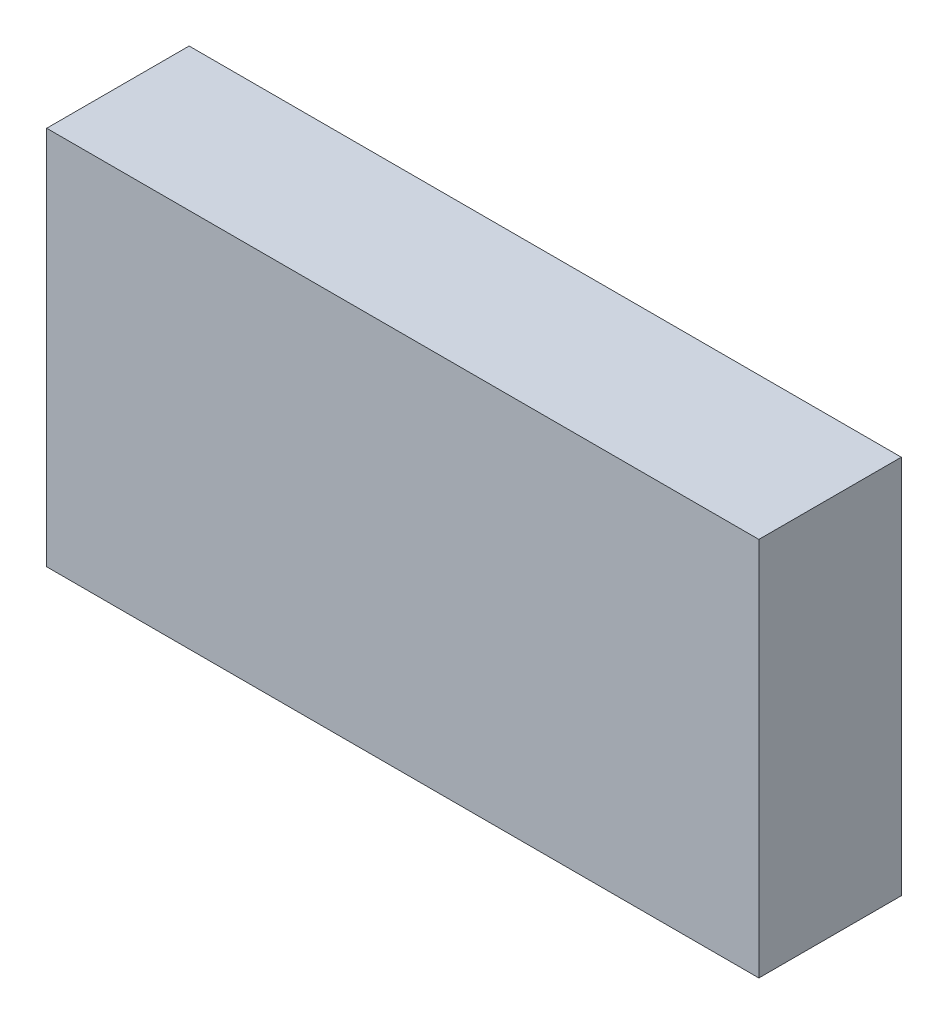
SolidWorks part; units mm, degrees
ref_plane "Front Plane" through (0, 0, 0) normal (0, 0, 1) x (1, 0, 0)
ref_plane "Top Plane" through (0, 0, 0) normal (0, 1, 0) x (1, 0, 0)
ref_plane "Right Plane" through (0, 0, 0) normal (1, 0, 0) x (0, 0, -1)
other "Configuration Table"
sketch "Sketch1" plane through (0, 0, 0) normal (0, 0, 1) x (1, 0, 0)
  line L1 (596, 73) -> (611, 73)
  line L2 (596, 73) -> (596, 81)
  line L3 (596, 81) -> (611, 81)
  line L4 (611, 73) -> (611, 81)
extrude "CEK_taze_miknatis_15x8x3_1" add sketch "Sketch1" against normal blind 3 separate body
